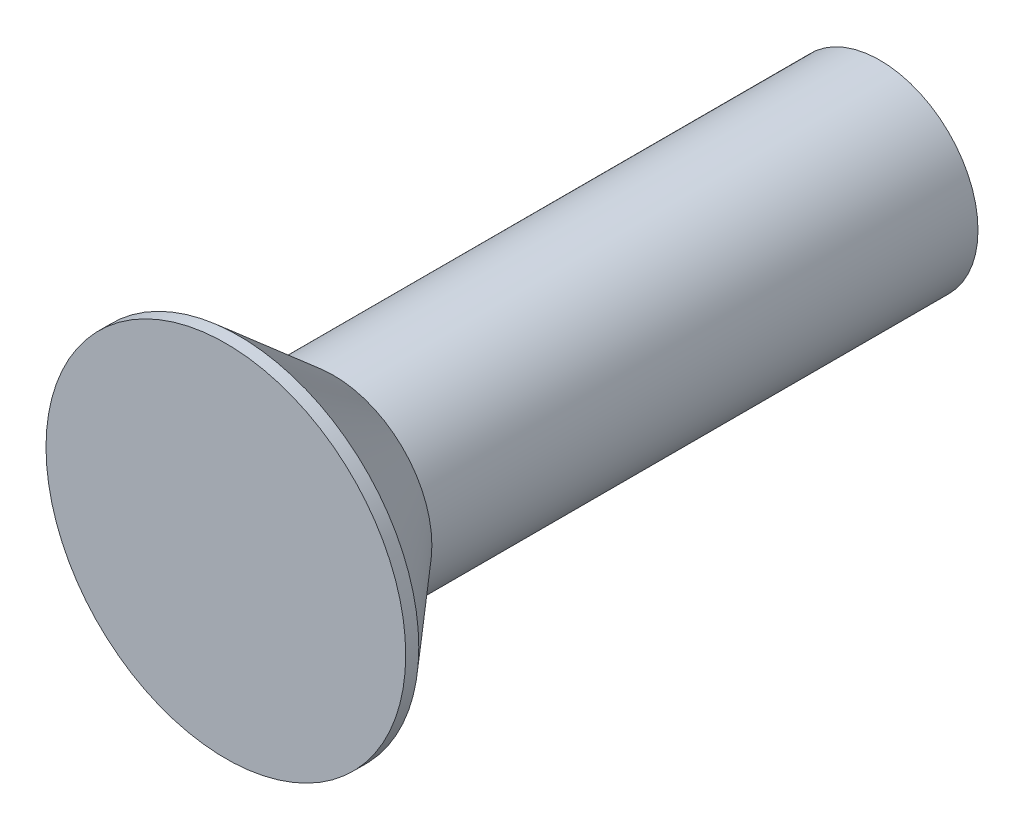
SolidWorks part; units mm, degrees
ref_plane "前视基准面" through (0, 0, 0) normal (0, 0, 1) x (1, 0, 0)
ref_plane "上视基准面" through (0, 0, 0) normal (0, 1, 0) x (1, 0, 0)
ref_plane "右视基准面" through (0, 0, 0) normal (1, 0, 0) x (0, 0, -1)
other "Configuration Table"
sketch "草图1" plane through (0, 0, 0) normal (1, 0, 0) x (0, 0, -1)
  line L0 (-5.3523, 0) -> (9.2568, 0) construction
  line L1 (-2.9125, 2.75) -> (-1.4625, 1.5)
  line L4 (-1.4625, 1.5) -> (6.8875, 1.5)
  line L5 (6.8875, 0) -> (6.8875, 1.5)
  line L6 (-1.4625, -1.5) -> (6.8875, 1.5) construction
  line L7 (-1.4625, 1.5) -> (6.8875, -1.5) construction
  line L9 (-3.1125, 0) -> (-3.1125, 2.75)
  line L10 (-3.1125, 2.75) -> (-2.9125, 2.75)
  line L12 (-3.1125, -2.75) -> (-2.9125, 2.75) construction
  line L13 (-3.1125, 2.75) -> (-2.9125, -2.75) construction
  line L15 (6.8875, 0) -> (-3.1125, 0)
  point P3 (2.7125, 0)
  point P8 (-3.0125, 0)
  dimension "D1" = 3
  dimension "D2" = 0.2
  dimension "D3" = 5.5
  dimension "D4" = 10
revolve "旋转4" add sketch "草图1" angle 360 about L0
